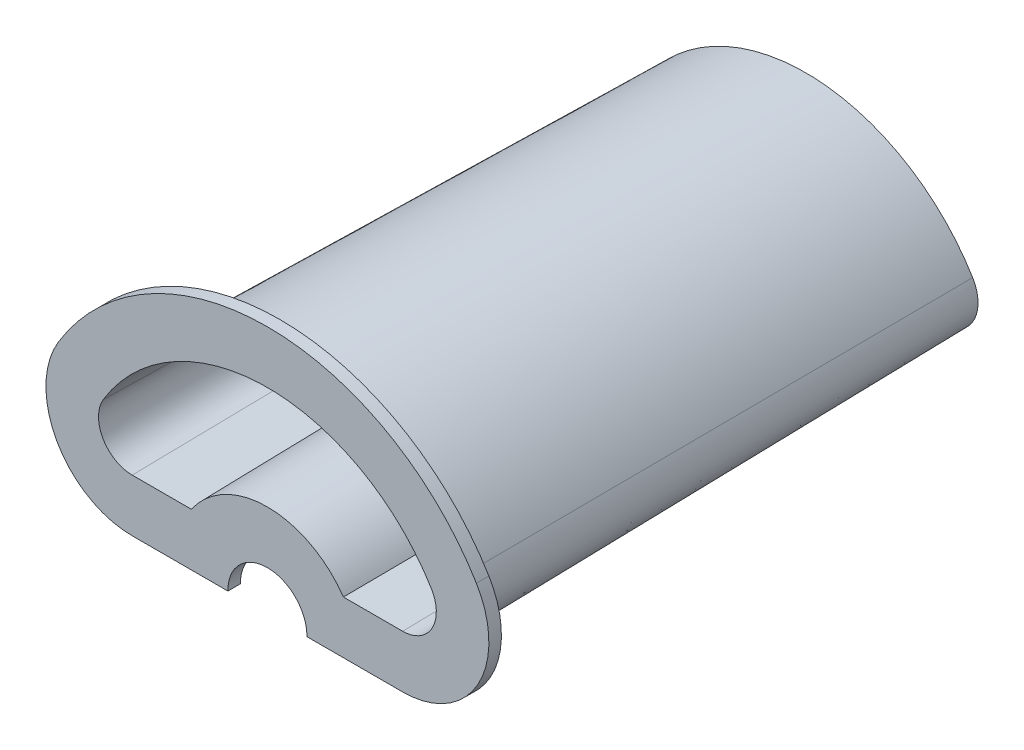
SolidWorks part; units mm, degrees
material "PBT General Purpose"
ref_plane "Plane1" through (0, 0, 0) normal (0, 0, 1) x (1, 0, 0)
ref_plane "Plane2" through (0, 0, 0) normal (0, 1, 0) x (1, 0, 0)
ref_plane "Plane3" through (0, 0, 0) normal (1, 0, 0) x (0, 0, -1)
sketch "Sketch1" plane through (0, 0, 0) normal (0, 0, 1) x (1, 0, 0)
  line L1 (27, 10.3944) -> (13.5, 10.3944)
  line L2 (27, 10.3944) -> (13.7931, 10.3944)
  line L3 (-27, 10.3944) -> (-13.5, 10.3944)
  line L4 (-27, 10.3944) -> (-13.7931, 10.3944)
  arc A3 (34.887, 24.4043) -> (-34.887, 24.4043) centre (0, 3.2392) ccw
  arc A4 (34.887, 24.4043) -> (-34.887, 24.4043) centre (0, 3.2392) ccw
  arc A5 (27, 10.3944) -> (34.887, 24.4043) centre (27, 19.6194) ccw
  arc A6 (27, 10.3944) -> (34.887, 24.4043) centre (27, 19.6194) ccw
  arc A7 (13.9386, 10.1345) -> (-13.9386, 10.1345) centre (0, 2.5038) ccw
  arc A8 (13.7931, 10.3944) -> (-13.7931, 10.3944) centre (0, 2.5038) ccw
  arc A9 (-34.887, 24.4043) -> (-27, 10.3944) centre (-27, 19.6194) ccw
  arc A10 (-34.887, 24.4043) -> (-27, 10.3944) centre (-27, 19.6194) ccw
  dimension "D1" = 0.5
  dimension "D2" = 0.5
  dimension "D3" = 0.5
  dimension "D4" = 0.5
  dimension "D5" = 0.5
  dimension "D6" = 0.5
extrude "Base-Extrude" add sketch "Sketch1" against normal blind 105 draft 1
sketch "Sketch2" plane through (0, 0, 0) normal (0, 0, 1) x (1, 0, 0)
  line L2 (7.8899, 2.3944) -> (27, 2.3944)
  line L3 (-27, 2.3944) -> (-7.8899, 2.3944)
  line L4 (7.8899, 2.3944) -> (27, 2.3944)
  line L5 (-27, 2.3944) -> (-7.8899, 2.3944)
  arc A4 (7.8899, 2.3944) -> (-7.8899, 2.3944) centre (0, 2.5038) ccw
  arc A5 (27, 2.3944) -> (41.7268, 28.5538) centre (27, 19.6194) ccw
  arc A6 (41.7268, 28.5538) -> (-41.7268, 28.5538) centre (0, 3.2392) ccw
  arc A7 (-41.7268, 28.5538) -> (-27, 2.3944) centre (-27, 19.6194) ccw
  arc A8 (7.8899, 2.3944) -> (-7.8899, 2.3944) centre (0, 2.5038) ccw
  arc A9 (27, 2.3944) -> (41.7268, 28.5538) centre (27, 19.6194) ccw
  arc A10 (41.7268, 28.5538) -> (-41.7268, 28.5538) centre (0, 3.2392) ccw
  arc A11 (-41.7268, 28.5538) -> (-27, 2.3944) centre (-27, 19.6194) ccw
  dimension "D1" = 8
extrude "Boss-Extrude1" add sketch "Sketch2" along normal blind 2.5
sketch "Sketch3" plane through (0, 0, 2.5) normal (0, 0, 1) x (1, 0, 0)
  line L2 (15.174, 12.8944) -> (27, 12.8944)
  line L3 (-27, 12.8944) -> (-15.174, 12.8944)
  line L4 (15.174, 12.8944) -> (27, 12.8944)
  line L5 (-27, 12.8944) -> (-15.174, 12.8944)
  arc A4 (15.174, 12.8944) -> (-15.174, 12.8944) centre (0, 2.5038) ccw
  arc A5 (27, 12.8944) -> (32.7496, 23.1076) centre (27, 19.6194) ccw
  arc A6 (32.7496, 23.1076) -> (-32.7496, 23.1076) centre (0, 3.2392) ccw
  arc A7 (-32.7496, 23.1076) -> (-27, 12.8944) centre (-27, 19.6194) ccw
  arc A8 (15.174, 12.8944) -> (-15.174, 12.8944) centre (0, 2.5038) ccw
  arc A9 (27, 12.8944) -> (32.7496, 23.1076) centre (27, 19.6194) ccw
  arc A10 (32.7496, 23.1076) -> (-32.7496, 23.1076) centre (0, 3.2392) ccw
  arc A11 (-32.7496, 23.1076) -> (-27, 12.8944) centre (-27, 19.6194) ccw
  dimension "D1" = 10.5
split line "Split Line1"
sketch "Sketch4" plane through (0, 0, 2.5) normal (0, 0, 1) x (1, 0, 0)
  line L2 (-27, 12.8944) -> (-15.174, 12.8944)
  line L3 (15.174, 12.8944) -> (27, 12.8944)
  line L4 (-27, 12.8944) -> (-15.174, 12.8944)
  line L5 (15.174, 12.8944) -> (27, 12.8944)
  arc A4 (15.174, 12.8944) -> (-15.174, 12.8944) centre (0, 2.5038) ccw
  arc A5 (27, 12.8944) -> (32.7496, 23.1076) centre (27, 19.6194) ccw
  arc A6 (32.7496, 23.1076) -> (-32.7496, 23.1076) centre (0, 3.2392) ccw
  arc A7 (-32.7496, 23.1076) -> (-27, 12.8944) centre (-27, 19.6194) ccw
  arc A8 (15.174, 12.8944) -> (-15.174, 12.8944) centre (0, 2.5038) ccw
  arc A9 (27, 12.8944) -> (32.7496, 23.1076) centre (27, 19.6194) ccw
  arc A10 (32.7496, 23.1076) -> (-32.7496, 23.1076) centre (0, 3.2392) ccw
  arc A11 (-32.7496, 23.1076) -> (-27, 12.8944) centre (-27, 19.6194) ccw
  dimension "D1" = 0
extrude "Cut-Extrude1" cut sketch "Sketch4" against normal offset from surface 2.5 draft 1
sketch "Sketch5" plane through (0, 0, -105) normal (0, 0, -1) x (-1, 0, 0)
  line L0 (0, 0) -> (0, 77.112) construction
  circle A0 centre (-29.7171, 16.873) radius 1.4
  dimension "D1" = 2.8
extrude "Boss-Extrude2" add sketch "Sketch5" along normal blind 3 draft 45
